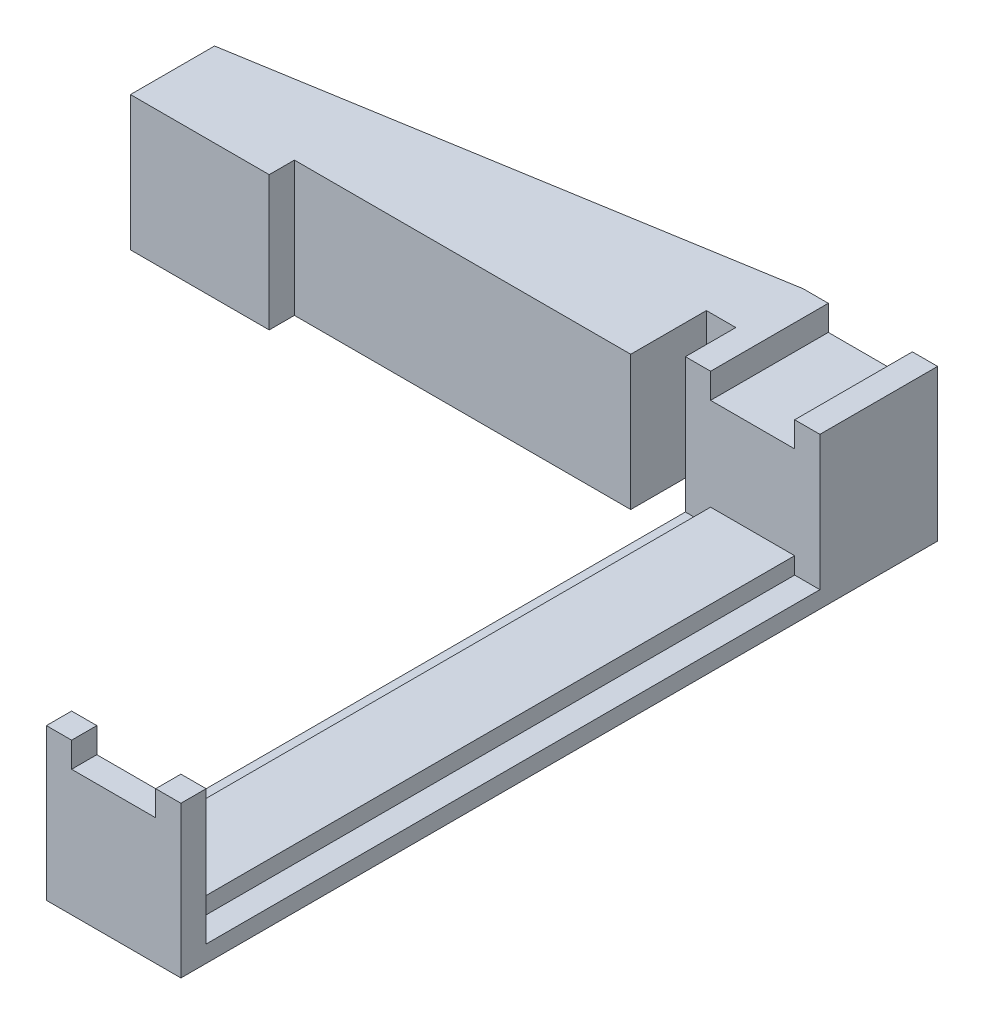
SolidWorks part; units mm, degrees
material "6061 Alloy"
ref_plane "Front Plane" through (0, 0, 0) normal (0, 0, 1) x (1, 0, 0)
ref_plane "Top Plane" through (0, 0, 0) normal (0, 1, 0) x (1, 0, 0)
ref_plane "Right Plane" through (0, 0, 0) normal (1, 0, 0) x (0, 0, -1)
sketch "Sketch1" plane through (0, 0, 0) normal (0, 1, 0) x (1, 0, 0)
  line L0 (0, 0) -> (30, 0)
  line L1 (30, 0) -> (30, -35)
  line L2 (30, -35) -> (38, -35)
  line L3 (38, -35) -> (38, 10)
  line L4 (38, 10) -> (30, 10)
  line L5 (30, 10) -> (0, 5)
  line L6 (0, 5) -> (0, 0)
  dimension "D1" = 30
  dimension "D2" = 45
  dimension "D3" = 5
  dimension "D4" = 8
  dimension "D5" = 10
extrude "Boss-Extrude1" add sketch "Sketch1" along normal blind 9
sketch "Sketch2" plane through (0, 9, 0) normal (0, 1, 0) x (1, 0, 0)
  line L0 (38, -35) -> (38, 10) construction
  line L1 (30, 3) -> (38, 3)
  line L2 (30, 3) -> (30, -33.5)
  line L3 (30, -33.5) -> (38, -33.5)
  line L4 (38, 3) -> (38, -33.5)
  line L5 (0, 0) -> (30, 0) construction
  line L6 (30, -35) -> (38, -35) construction
  dimension "D1" = 3
  dimension "D2" = 1.5
  dimension "D3" = 8
extrude "Cut-Extrude2" cut sketch "Sketch2" against normal blind 7
sketch "Sketch3" plane through (0, 2, 0) normal (0, 1, 0) x (1, 0, 0)
  line L0 (30, -33.5) -> (38, -33.5) construction
  line L1 (38, 3) -> (36.5, 3)
  line L2 (38, 3) -> (38, -33.5)
  line L3 (38, -33.5) -> (36.5, -33.5)
  line L4 (36.5, 3) -> (36.5, -33.5)
  line L6 (30, 3) -> (31.5, 3)
  line L7 (30, 3) -> (30, -33.5)
  line L8 (30, -33.5) -> (31.5, -33.5)
  line L9 (31.5, 3) -> (31.5, -33.5)
  dimension "D1" = 1.5
  dimension "D2" = 1.5
extrude "Cut-Extrude3" cut sketch "Sketch3" against normal blind 1
sketch "Sketch4" plane through (0, 9, 0) normal (0, 1, 0) x (1, 0, 0)
  line L1 (30, 0) -> (28.25, 0)
  line L2 (30, 0) -> (30, 3)
  line L3 (30, 3) -> (28.25, 3)
  line L4 (28.25, 0) -> (28.25, 3)
  dimension "D1" = 1.75
extrude "Cut-Extrude4" cut sketch "Sketch4" against normal through all
sketch "Sketch5" plane through (0, 9, 0) normal (0, 1, 0) x (1, 0, 0)
  line L0 (38, 10) -> (30, 10) construction
  line L1 (31.5, 10) -> (36.5, 10)
  line L2 (31.5, 10) -> (31.5, -35)
  line L3 (31.5, -35) -> (36.5, -35)
  line L4 (36.5, 10) -> (36.5, -35)
  line L5 (30, -35) -> (38, -35) construction
  line L6 (31.5, -33.5) -> (31.5, 3) construction
  line L7 (36.5, 3) -> (36.5, -33.5) construction
extrude "Cut-Extrude5" cut sketch "Sketch5" against normal blind 1.5
sketch "Sketch6" plane through (0, 0, 0) normal (0, -1, 0) x (-1, 0, 0)
  line L0 (-28.25, 0) -> (-28.25, 9.7083)
  line L1 (-30, 10) -> (0, 5) construction
  line L2 (-28.25, 9.7083) -> (0, 5)
  line L3 (0, 5) -> (0, 0)
  line L4 (0, 0) -> (-28.25, 0)
extrude "Cut-Extrude6" cut sketch "Sketch6" against normal blind 1
sketch "Sketch7" plane through (0, 9, 0) normal (0, 1, 0) x (1, 0, 0)
  line L0 (0, 0) -> (28.25, 0) construction
  line L1 (8.25, 0) -> (28.25, 0)
  line L2 (8.25, 0) -> (8.25, 1.5)
  line L3 (8.25, 1.5) -> (28.25, 1.5)
  line L4 (28.25, 0) -> (28.25, 1.5)
  line L5 (28.25, 3) -> (28.25, 0) construction
  dimension "D1" = 20
extrude "Cut-Extrude7" cut sketch "Sketch7" against normal through all
sketch "Sketch8" plane through (0, 9, 0) normal (0, 1, 0) x (1, 0, 0)
  line L0 (31.5, 3) -> (28.25, 3) construction
  line L1 (28.25, 3) -> (30, 3)
  line L2 (28.25, 3) -> (28.25, 6)
  line L3 (28.25, 6) -> (30, 6)
  line L4 (30, 3) -> (30, 6)
  dimension "D1" = 3
extrude "Cut-Extrude8" cut sketch "Sketch8" against normal through all
